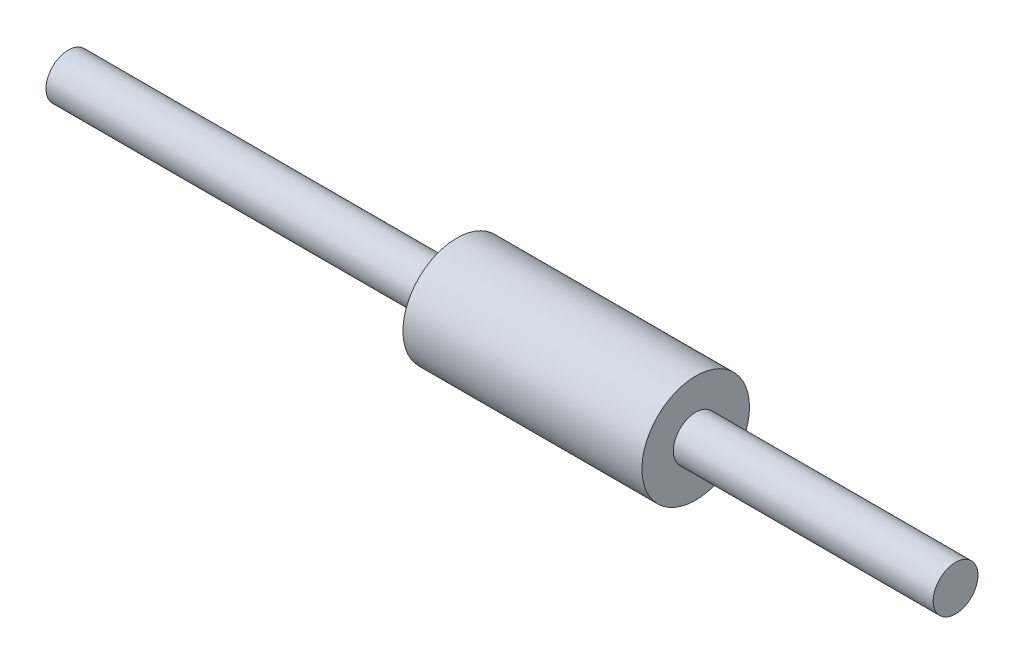
SolidWorks part; units mm, degrees
ref_plane "Front Plane" through (0, 0, 0) normal (0, 0, 1) x (1, 0, 0)
ref_plane "Top Plane" through (0, 0, 0) normal (0, 1, 0) x (1, 0, 0)
ref_plane "Right Plane" through (0, 0, 0) normal (1, 0, 0) x (0, 0, -1)
sketch "Sketch1" plane through (0, 0, 0) normal (0, 0, 1) x (1, 0, 0)
  line L0 (196.3562, 0) -> (-196.3562, 0) construction
  line L3 (127, 7.5) -> (-170, 7.5)
  line L4 (0, -42.6677) -> (0, 42.6677) construction
  line L7 (127, 7.5) -> (127, 0)
  line L8 (127, 0) -> (-127, 0)
  line L9 (-170, 7.5) -> (-170, 6.5)
  line L10 (-170, 6.5) -> (-127, 6.5)
  line L11 (-127, 6.5) -> (-127, 0)
  line L12 (-40, 18) -> (40, 18)
  line L13 (-40, 18) -> (-40, 7.5)
  line L14 (40, 18) -> (40, 7.5)
  point P3 (0, 18)
  point P10 (0, 0)
  dimension "D1" = 127
  dimension "D3" = 43
  dimension "D4" = 15
  dimension "D5" = 13
  dimension "D6" = 36
  dimension "D7" = 80
  dimension "D2" = 127
revolve "Revolve1" add sketch "Sketch1" angle 360 about L0
equation "\"D2@Sketch1\"=\"D1@Sketch1\""
